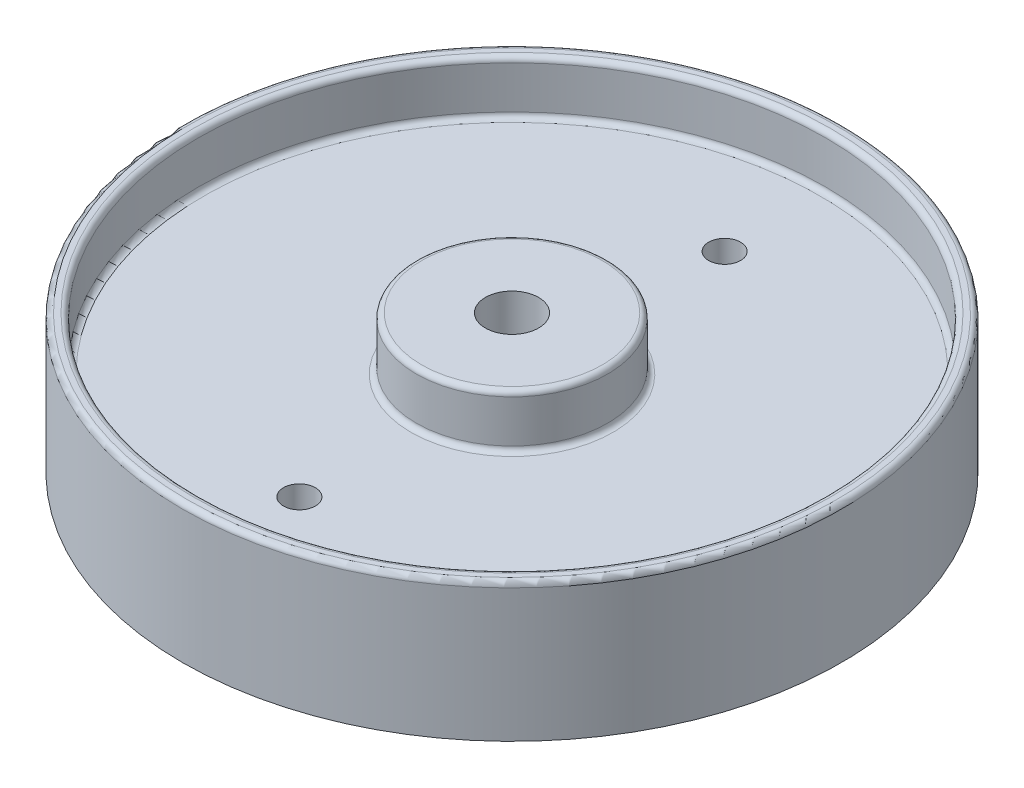
SolidWorks part; units mm, degrees
ref_plane "Plan de face" through (0, 0, 0) normal (0, 0, 1) x (1, 0, 0)
ref_plane "Plan de dessus" through (0, 0, 0) normal (0, 1, 0) x (1, 0, 0)
ref_plane "Plan de droite" through (0, 0, 0) normal (1, 0, 0) x (0, 0, -1)
sketch "Esquisse1" plane through (0, 0, 0) normal (0, 1, 0) x (1, 0, 0)
  circle A0 centre (0, 0) radius 2.5
  circle A1 centre (0, 0) radius 31
  dimension "D1" = 62
  dimension "D2" = 5
extrude "Extrusion1" add sketch "Esquisse1" along normal blind 13
sketch "Esquisse2" plane through (0, 13, 0) normal (0, 1, 0) x (1, 0, 0)
  circle A0 centre (0, 0) radius 9
  circle A1 centre (0, 0) radius 29.5
  dimension "D1" = 18
  dimension "D2" = 59
extrude "Enlèv. mat.-Extru.1" cut sketch "Esquisse2" against normal blind 5
fillet "Congé1" radius 0.5 5 edges at (0, 13, 31) (0, 13, 9) (0, 13, 29.5) (0, 8, 29.5) (0, 8, 9)
sketch "Esquisse3" plane through (0, 8, 0) normal (0, 1, 0) x (1, 0, 0)
  line L0 (0, 20) -> (0, -20) construction
  circle A0 centre (0, 20) radius 1.5
  circle A1 centre (0, -20) radius 1.5
  dimension "D1" = 3
  dimension "D2" = 40
extrude "Enlèv. mat.-Extru.2" cut sketch "Esquisse3" against normal blind 5
